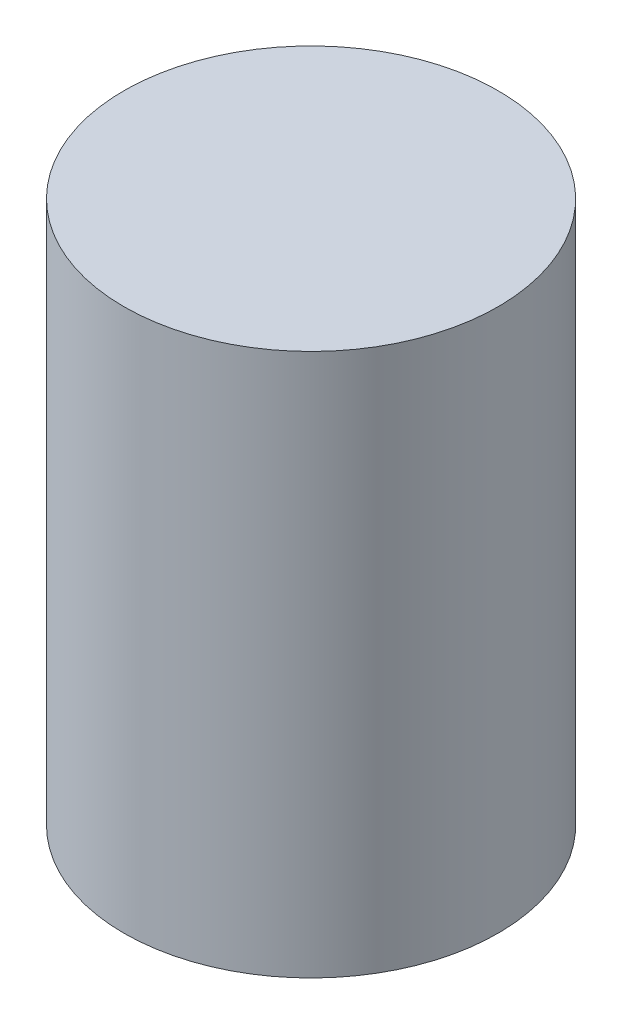
SolidWorks part; units mm, degrees
ref_plane "Płaszczyzna przednia" through (0, 0, 0) normal (0, 0, 1) x (1, 0, 0)
ref_plane "Płaszczyzna górna" through (0, 0, 0) normal (0, 1, 0) x (1, 0, 0)
ref_plane "Płaszczyzna prawa" through (0, 0, 0) normal (1, 0, 0) x (0, 0, -1)
sketch "Sketch1" plane through (0, 0, 0) normal (0, 1, 0) x (1, 0, 0)
  circle A0 centre (0, 0) radius 1
  dimension "D1" = 2
extrude "Boss-Extrude1" add sketch "Sketch1" along normal blind 2.9
